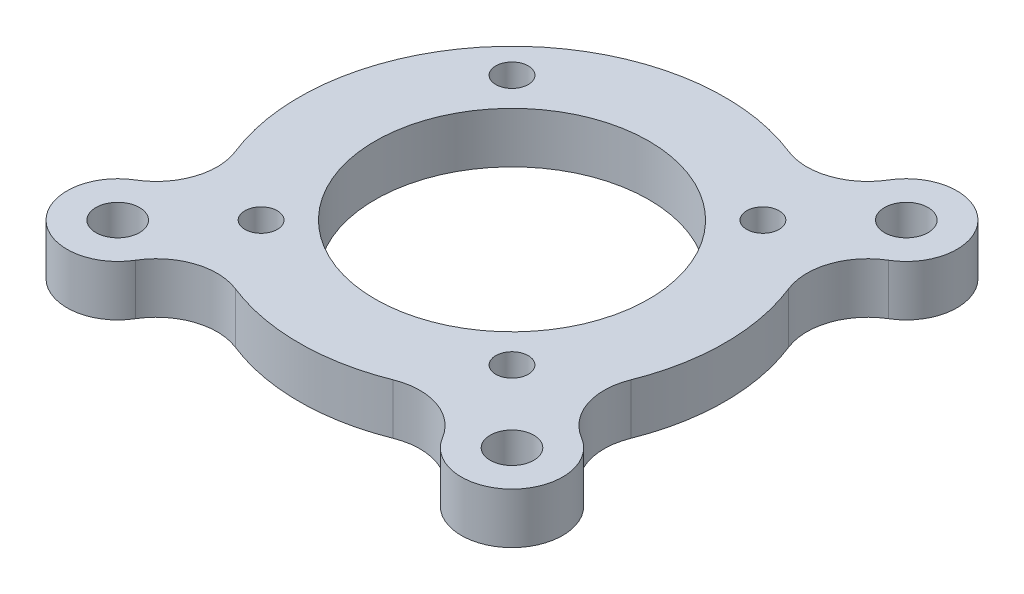
SolidWorks part; units mm, degrees
material "5052-H34"
ref_plane "正面" through (0, 0, 0) normal (0, 0, 1) x (1, 0, 0)
ref_plane "平面" through (0, 0, 0) normal (0, 1, 0) x (1, 0, 0)
ref_plane "右側面" through (0, 0, 0) normal (1, 0, 0) x (0, 0, -1)
sketch "ｽｹｯﾁ1" plane through (0, 0, 0) normal (0, 1, 0) x (1, 0, 0)
  line L0 (19.4454, 19.4454) -> (0, 0) construction
  line L4 (0, 0) -> (13.5, 0) construction
  line L5 (0, 0) -> (12.3744, 12.3744) construction
  circle A4 centre (0, 0) radius 13.5
  circle A5 centre (12.3744, 12.3744) radius 1.6
  circle A6 centre (12.3744, -12.3744) radius 1.6
  circle A7 centre (-12.3744, -12.3744) radius 1.6
  circle A8 centre (-12.3744, 12.3744) radius 1.6
  circle A9 centre (19.4454, 19.4454) radius 2.15
  arc A13 (19.5071, -7.7766) -> (19.5071, 7.7766) centre (0, 0) ccw
  arc A14 (22.0068, 15.1513) -> (15.1513, 22.0068) centre (19.4454, 19.4454) ccw
  arc A18 (15.1513, 22.0068) -> (7.7766, 19.5071) centre (9.9984, 25.0805) cw
  arc A19 (22.0068, 15.1513) -> (19.5071, 7.7766) centre (25.0805, 9.9984) ccw
  arc A20 (15.1513, -22.0068) -> (22.0068, -15.1513) centre (19.4454, -19.4454) ccw
  arc A21 (15.1513, -22.0068) -> (7.7766, -19.5071) centre (9.9984, -25.0805) ccw
  circle A22 centre (19.4454, -19.4454) radius 2.15
  arc A23 (22.0068, -15.1513) -> (19.5071, -7.7766) centre (25.0805, -9.9984) cw
  arc A24 (-22.0068, -15.1513) -> (-15.1513, -22.0068) centre (-19.4454, -19.4454) ccw
  arc A25 (-22.0068, -15.1513) -> (-19.5071, -7.7766) centre (-25.0805, -9.9984) ccw
  circle A26 centre (-19.4454, -19.4454) radius 2.15
  arc A27 (-15.1513, -22.0068) -> (-7.7766, -19.5071) centre (-9.9984, -25.0805) cw
  arc A32 (-7.7766, -19.5071) -> (7.7766, -19.5071) centre (0, 0) ccw
  arc A33 (-7.7766, -19.5071) -> (7.7766, -19.5071) centre (0, 0) ccw
  arc A34 (-7.7766, -19.5071) -> (7.7766, -19.5071) centre (0, 0) ccw
  arc A35 (7.7766, 19.5071) -> (-19.5071, -7.7766) centre (0, 0) ccw
  arc A36 (-15.1513, 22.0068) -> (-22.0068, 15.1513) centre (-19.4454, 19.4454) ccw [skipped]
  circle A37 centre (-19.4454, 19.4454) radius 2.15 [skipped]
  arc A38 (-15.1513, 22.0068) -> (-7.7766, 19.5071) centre (-9.9984, 25.0805) ccw [skipped]
  arc A39 (-22.0068, 15.1513) -> (-19.5071, 7.7766) centre (-25.0805, 9.9984) cw [skipped]
  arc A40 (19.5071, -7.7766) -> (19.5071, 7.7766) centre (0, 0) ccw
  arc A41 (19.5071, -7.7766) -> (19.5071, 7.7766) centre (0, 0) ccw
  arc A42 (7.7766, 19.5071) -> (-19.5071, -7.7766) centre (0, 0) ccw
  arc A43 (7.7766, 19.5071) -> (-19.5071, -7.7766) centre (0, 0) ccw
  point P17 (0, 0)
  point P24 (0, 0)
  point P33 (0, 0)
  dimension "D2" = 10
  dimension "D4" = 27.5
  dimension "D6" = 27
  dimension "D8" = 3.2
  dimension "D3" = 4.3
  dimension "D12" = 42
  dimension "D14" = 6
  dimension "D7" = 45
  dimension "D9" = 17.5
  dimension "D11" = 45
  dimension "D10" = 4
extrude "ﾎﾞｽ - 押し出し1" add sketch "ｽｹｯﾁ1" along normal blind 5 contours A18 A35 A25 A24 A27 A32 A21 A20 A23 A13 A19 A14 A4 A5 A6 A7 A8 A9 A22 A26
